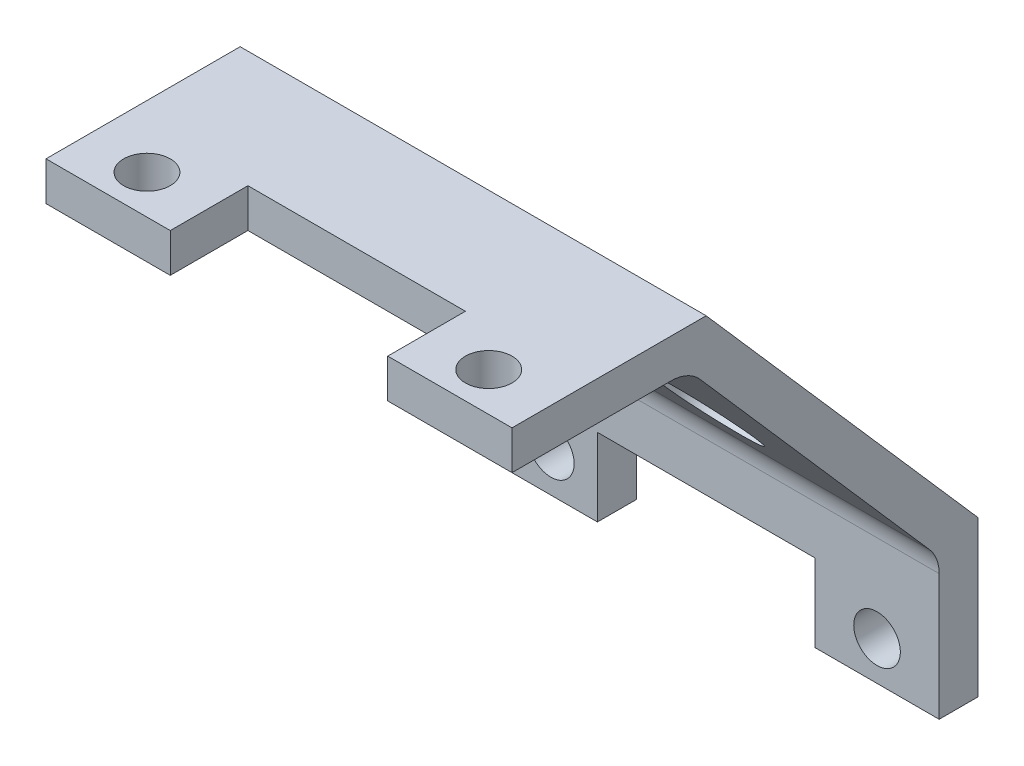
SolidWorks part; units mm, degrees
ref_plane "Front Plane" through (0, 0, 0) normal (0, 0, 1) x (1, 0, 0)
ref_plane "Top Plane" through (0, 0, 0) normal (0, 1, 0) x (1, 0, 0)
ref_plane "Right Plane" through (0, 0, 0) normal (1, 0, 0) x (0, 0, -1)
sketch "Sketch1" plane through (0, 0, 0) normal (1, 0, 0) x (0, 0, -1)
  line L0 (-55, 60) -> (-55, 55)
  line L1 (-55, 55) -> (-34.5377, 55)
  line L2 (-30.7748, 53.2925) -> (-1.2371, 19.5352)
  line L3 (0, 16.2426) -> (0, 0)
  line L4 (0, 0) -> (5, 0)
  line L5 (5, 0) -> (5, 20)
  line L6 (5, 20) -> (-30, 60)
  line L7 (-30, 60) -> (-55, 60)
  arc A0 (-30.7748, 53.2925) -> (-34.5377, 55) centre (-34.5377, 50) ccw
  arc A1 (0, 16.2426) -> (-1.2371, 19.5352) centre (-5, 16.2426) ccw
  point P10 (-32.2688, 55)
  point P13 (31.4112, 20.1016)
  point P15 (0, 0)
  point P16 (0, 0)
  point P17 (0, 0)
  dimension "D5" = 5
  dimension "D6" = 5
  dimension "D1" = 60
  dimension "D2" = 60
  dimension "D3" = 20
  dimension "D4" = 25
  dimension "D7" = 5
  dimension "D8" = 5
extrude "Boss-Extrude1" add sketch "Sketch1" along normal blind 60
sketch "Sketch2" plane through (0, 11.1504, -12.7434) normal (0, 0.6585, -0.7526) x (-1, 0, 0)
  line L0 (0, 11.759) -> (0, 64.9097) construction
  line L6 (-60, 64.9097) -> (0, 64.9097) construction
  circle A0 centre (-40, 48.3347) radius 6
  circle A1 centre (-40, 28.3347) radius 6
  circle A2 centre (-20, 48.3347) radius 6
  circle A3 centre (-20, 28.3347) radius 6
  point P4 (-41.5374, 37.6039)
  point P7 (-20.6125, 53.0987)
  point P10 (-20.6125, 37.6039)
  point P11 (0, 0)
  point P12 (0, 0)
  point P13 (0, 0)
  point P14 (0, 0)
  point P17 (0, 0)
  point P18 (-20, 48.3347)
  dimension "D1" = 12
  dimension "D5" = 16.575
  dimension "D2" = 20
  dimension "D3" = 20
  dimension "D4" = 20
extrude "Cut-Extrude1" cut sketch "Sketch2" against normal up to next
sketch "Sketch3" plane through (0, 0, -5) normal (0, 0, -1) x (-1, 0, 0)
  line L0 (-44, 0) -> (-44, 10)
  line L1 (-60, 0) -> (0, 0) construction
  line L2 (-44, 10) -> (-16, 10)
  line L3 (-16, 10) -> (-16, 0)
  line L4 (-44, 0) -> (-16, 0)
  line L5 (-60, 0) -> (-60, 20) construction
  line L6 (0, 0) -> (0, 20) construction
  circle A0 centre (-52, 5) radius 3
  circle A1 centre (-10, 5) radius 3
  point P8 (-50.4449, 4.2569)
  point P11 (-6.5834, 4.0799)
  point P12 (0, 0)
  point P13 (0, 0)
  dimension "D1" = 6
  dimension "D2" = 8
  dimension "D3" = 5
  dimension "D4" = 28
  dimension "D5" = 16
  dimension "D6" = 10
  dimension "D7" = 10
extrude "Cut-Extrude2" cut sketch "Sketch3" against normal up to next
sketch "Sketch4" plane through (0, 60, 0) normal (0, 1, 0) x (1, 0, 0)
  line L0 (16, -55) -> (16, -45)
  line L1 (60, -55) -> (0, -55) construction
  line L2 (16, -45) -> (44, -45)
  line L3 (44, -45) -> (44, -55)
  line L4 (44, -55) -> (16, -55)
  line L5 (0, -30) -> (0, -55) construction
  line L6 (60, -30) -> (60, -55) construction
  circle A0 centre (8, -50) radius 3
  circle A1 centre (52, -50) radius 3
  point P12 (52.0352, -50)
  point P13 (0, 0)
  dimension "D1" = 6
  dimension "D2" = 8
  dimension "D3" = 5
  dimension "D4" = 28
  dimension "D5" = 10
  dimension "D6" = 16
  dimension "D7" = 8
extrude "Cut-Extrude3" cut sketch "Sketch4" against normal blind 60
